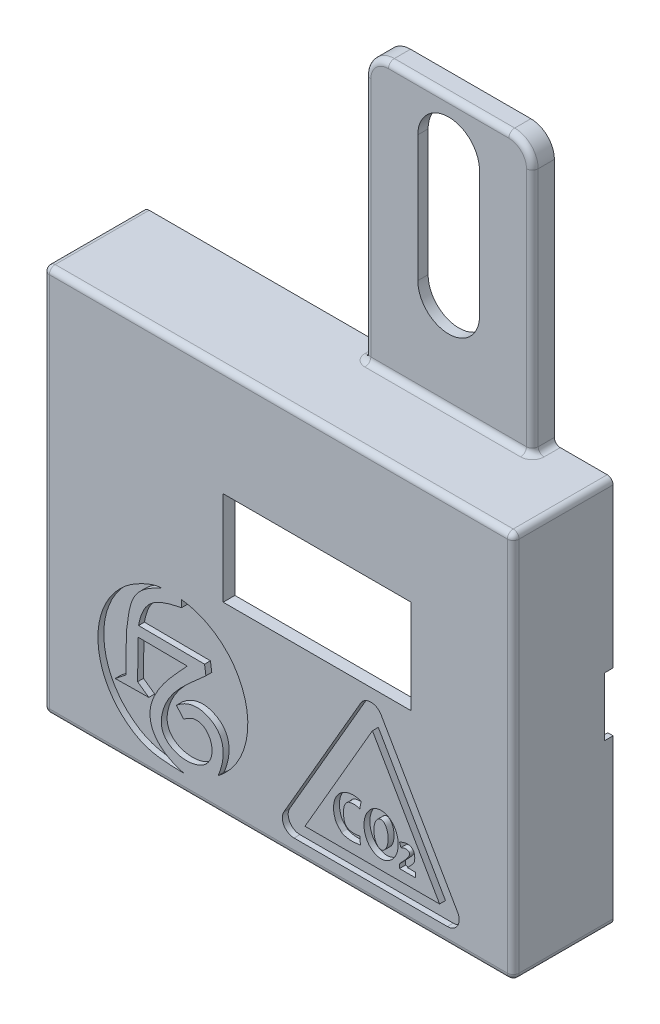
SolidWorks part; units mm, degrees
ref_plane "Front Plane" through (0, 0, 0) normal (0, 0, 1) x (1, 0, 0)
ref_plane "Top Plane" through (0, 0, 0) normal (0, 1, 0) x (1, 0, 0)
ref_plane "Right Plane" through (0, 0, 0) normal (1, 0, 0) x (0, 0, -1)
sketch "Croquis1" plane through (0, 0, 0) normal (0, 0, 1) x (1, 0, 0)
  line L3 (-40, -30.5) -> (40, -30.5)
  line L10 (-40, 35.5) -> (40, 35.5)
  line L12 (-40, 35.5) -> (-40, -30.5)
  line L14 (40, -30.5) -> (40, 35.5)
  point P1 (0, 0)
  dimension "D2" = 40
  dimension "D3" = 66
  dimension "D1" = 80
  dimension "D4" = 35.5
extrude "Saliente-Extruir2" add sketch "Croquis1" along normal blind 17
shell "Vaciado7" thickness 2
sketch "Croquis12" plane through (0, 0, 17) normal (0, 0, 1) x (1, 0, 0)
  line L1 (-9.4, 17) -> (22.6, 17)
  line L2 (-9.4, 17) -> (-9.4, 1)
  line L3 (-9.4, 1) -> (22.6, 1)
  line L4 (22.6, 17) -> (22.6, 1)
  line L5 (-9.4, 17) -> (22.6, 1) construction
  line L6 (-9.4, 1) -> (22.6, 17) construction
  line L9 (40, 35.5) -> (-40, 35.5) construction
  line L11 (40, -30.5) -> (40, 35.5) construction
  point P0 (6.6, 9)
  dimension "D1" = 17.4
  dimension "D2" = 32
  dimension "D3" = 16
  dimension "D4" = 18.5
extrude "Cortar-Extruir9" cut sketch "Croquis12" against normal up to next
sketch "Croquis29" plane through (0, 0, 0) normal (0, 0, -1) x (-1, 0, 0)
  line L9 (-1.5, 77.5) -> (-1.5, 35.5)
  line L10 (-5.5, 81.5) -> (-26, 81.5)
  line L14 (-15.75, 73.25) -> (-15.75, 51.75) construction
  line L15 (-10.5, 73.25) -> (-10.5, 51.75)
  line L16 (-21, 73.25) -> (-21, 51.75)
  line L17 (-30, 35.5) -> (-30, 77.5)
  line L19 (-1.5, 35.5) -> (-30, 35.5)
  line L20 (-40, 35.5) -> (40, 35.5) construction
  line L21 (-40, -30.5) -> (-40, 35.5) construction
  arc A8 (-10.5, 73.25) -> (-21, 73.25) centre (-15.75, 73.25) ccw
  arc A9 (-21, 51.75) -> (-10.5, 51.75) centre (-15.75, 51.75) ccw
  arc A10 (-30, 77.5) -> (-26, 81.5) centre (-26, 77.5) cw
  arc A11 (-1.5, 77.5) -> (-5.5, 81.5) centre (-5.5, 77.5) ccw
  point P2 (-15.75, 62.5)
  dimension "D3" = 10
  dimension "D4" = 4
  dimension "D7" = 5.25
  dimension "D2" = 4
  dimension "D1" = 28.5
  dimension "D5" = 46
  dimension "D6" = 21.5
  dimension "D8" = 14.25
  dimension "D9" = 8.25
extrude "Saliente-Extruir3" add sketch "Croquis29" against normal blind 3.75
sketch "Croquis14" plane through (0, 0, 0) normal (0, 0, -1) x (-1, 0, 0)
  line L8 (39.1, 34.6) -> (-2.4, 34.6)
  line L10 (-29.1, 34.6) -> (-39.1, 34.6)
  line L14 (39.1, 34.6) -> (-2.4, 34.6)
  line L16 (-29.1, 34.6) -> (-39.1, 34.6)
  line L17 (-39.1, -29.6) -> (39.1, -29.6)
  line L21 (-39.1, 34.6) -> (-39.1, -29.6)
  line L22 (-39.1, 34.6) -> (-39.1, -29.6)
  line L23 (39.1, -29.6) -> (39.1, 34.6)
  line L25 (-39.1, -29.6) -> (39.1, -29.6)
  line L28 (39.1, -29.6) -> (39.1, 34.6)
  line L33 (-2.4, 34.6) -> (-2.4, 77.5)
  line L34 (-2.4, 34.6) -> (-2.4, 77.5)
  line L35 (-5.5, 80.6) -> (-26, 80.6)
  line L36 (-5.5, 80.6) -> (-26, 80.6)
  line L37 (-29.1, 77.5) -> (-29.1, 34.6)
  line L38 (-29.1, 77.5) -> (-29.1, 34.6)
  arc A2 (-2.4, 77.5) -> (-5.5, 80.6) centre (-5.5, 77.5) ccw
  arc A9 (-2.4, 77.5) -> (-5.5, 80.6) centre (-5.5, 77.5) ccw
  arc A11 (-26, 80.6) -> (-29.1, 77.5) centre (-26, 77.5) ccw
  arc A12 (-26, 80.6) -> (-29.1, 77.5) centre (-26, 77.5) ccw
  dimension "D1" = 0.9
extrude "Cortar-Extruir11" cut sketch "Croquis14" against normal blind 2
sketch "Croquis16" plane through (-40, 0, 0) normal (-1, 0, 0) x (0, 0, 1)
  line L1 (2, -6.75) -> (12, -6.75)
  line L2 (2, -6.75) -> (2, -18.75)
  line L3 (2, -18.75) -> (12, -18.75)
  line L4 (12, -6.75) -> (12, -18.75)
  line L5 (2, -6.75) -> (12, -18.75) construction
  line L6 (2, -18.75) -> (12, -6.75) construction
  line L9 (17, 35.5) -> (17, -30.5) construction
  line L10 (17, -30.5) -> (0, -30.5) construction
  point P0 (7, -12.75)
  dimension "D1" = 5
  dimension "D2" = 11.75
  dimension "D3" = 12
  dimension "D4" = 10
extrude "Cortar-Extruir26" cut sketch "Croquis16" against normal up to next
sketch "Croquis19" plane through (0, 0, 17) normal (0, 0, 1) x (1, 0, 0)
  line L0 (105.4121, 47.0931) -> (337.4121, 47.0931) construction
  line L1 (-25.8792, -11.5578) -> (-25.9589, -18.0125)
  line L2 (-25.9589, -18.0125) -> (-27.7917, -19.4468)
  line L3 (-27.7917, -19.4468) -> (-22.0542, -19.3672)
  line L4 (-22.0542, -19.3672) -> (-23.9667, -18.0125)
  line L5 (-23.9667, -18.0125) -> (-23.887, -11.3984)
  line L6 (-23.887, -11.3984) -> (-15.5198, -11.4781)
  line L9 (-12.3323, -11.3187) -> (-12.5714, -9.725)
  line L10 (-12.5714, -9.725) -> (-23.8073, -9.6453)
  line L11 (-16.4761, -3.35) -> (-16.4761, -2.1547)
  line L12 (-17.3526, -18.1718) -> (-16.1573, -19.6062)
  arc A0 (-16.4761, -2.1547) -> (-10.2604, -25.025) centre (-17.9717, -14.8409) cw
  spline S0 degree 3 poles (-16.0776, -27.575) (-20.4729, -27.492) (-23.2734, -27.3961) (-26.6761, -24.2281) (-28.09, -22.9117) (-29.2916, -21.1122) (-29.9433, -19.2875) (-31.8667, -13.902) (-30.1633, -8.11) (-25.6401, -4.625) (-24.3726, -3.6484) (-21.5246, -2.1547) (-19.9026, -2.1547) knots 0 0 0 0 1 1 1 2 2 2 3 3 3 4 4 4 4
  spline S1 degree 3 poles (-19.9026, -2.1547) (-24.8924, -4.4832) (-25.2643, -6.27) (-25.8792, -11.5578) knots 0 0 0 0 1 1 1 1
  spline S2 degree 3 poles (-15.5198, -11.4781) (-17.5458, -13.7292) (-19.7899, -15.9184) (-21.0979, -18.65) (-23.283, -23.213) (-20.5069, -26.4677) (-16.0776, -27.575) knots 0 0 0 0 1 1 1 2 2 2 2
  spline S3 degree 3 poles (-10.2604, -25.025) (-9.0652, -22.1997) (-8.6121, -18.4678) (-12.2526, -17.0562) (-14.1508, -16.3202) (-15.9323, -16.9701) (-17.3526, -18.1718) knots 0 0 0 0 1 1 1 2 2 2 2
  spline S4 degree 3 poles (-16.1573, -19.6062) (-15.5995, -19.314) (-15.0975, -18.8713) (-14.4839, -18.7297) (-11.483, -18.0371) (-9.9609, -22.854) (-12.8104, -24.7062) (-15.4582, -26.4273) (-20.4502, -25.2692) (-19.9026, -21.2797) (-19.2896, -16.813) (-15.3841, -14.1357) (-12.3323, -11.3187) knots 0 0 0 0 1 1 1 2 2 2 3 3 3 4 4 4 4
  spline S5 degree 3 poles (-23.8073, -9.6453) (-22.9979, -5.2747) (-20.9378, -4.2423) (-16.4761, -3.35) knots 0 0 0 0 1 1 1 1
extrude "Cortar-Extruir18" cut sketch "Croquis19" against normal blind 1
sketch "Croquis20" plane through (0, 0, 17) normal (0, 0, 1) x (1, 0, 0)
  line L0 (-454.7792, 225.5349) -> (-56.1125, 225.5349) construction
  line L1 (14.0959, -16.6185) -> (13.8627, -17.8433)
  line L2 (13.8627, -21.8676) -> (13.9793, -23.1507)
  line L3 (21.9695, -22.4508) -> (23.3705, -22.4508)
  line L4 (23.3705, -22.4508) -> (23.3705, -23.2695)
  line L5 (23.3705, -23.2695) -> (20.6281, -23.2673)
  line L6 (20.8614, -20.0596) -> (20.6281, -19.3597)
  line L7 (16.0206, -5.2456) -> (27.4555, -25.0753)
  line L8 (27.4555, -25.0753) -> (4.531, -25.0753)
  line L9 (4.531, -25.0753) -> (16.0206, -5.2456)
  line L13 (17.4925, -2.1582) -> (30.5158, -24.7424)
  line L14 (28.7832, -27.7415) -> (2.6744, -27.7415)
  line L15 (0.9439, -24.7389) -> (14.0294, -2.1547)
  arc A0 (2.6744, -27.7415) -> (0.9439, -24.7389) centre (2.6744, -25.7415) cw
  arc A1 (30.5158, -24.7424) -> (28.7832, -27.7415) centre (28.7832, -25.7415) cw
  arc A2 (17.4925, -2.1582) -> (14.0294, -2.1547) centre (15.7599, -3.1573) ccw
  ellipse E0 centre (17.4962, -19.8248) end of major axis (17.4563, -23.3931) minor radius 2.9144
  ellipse E1 centre (17.4814, -19.8225) end of major axis (17.5087, -22.0549) minor radius 1.2154
  spline S0 degree 3 poles (13.9793, -23.1507) (12.8026, -23.2978) (11.8949, -23.4089) (10.8299, -22.9174) (10.78, -22.8943) (10.7521, -22.8396) (10.7132, -22.8007) (10.3295, -22.417) (9.997, -22.1807) (9.7801, -21.6926) (8.9336, -19.7881) (9.4906, -17.4289) (11.4714, -16.6185) (12.3307, -16.267) (13.2427, -16.2773) (14.0959, -16.6185) knots 0 0 0 0 1 1 1 2 2 2 3 3 3 4 4 4 5 5 5 5
  spline S1 degree 3 poles (13.8627, -17.8433) (13.6099, -17.785) (13.3631, -17.6875) (13.1045, -17.6684) (12.8323, -17.6482) (12.5584, -17.6906) (12.2879, -17.7267) (10.871, -17.9156) (10.9607, -20.2139) (11.2965, -21.1094) (11.6855, -22.1468) (13.0408, -22.0046) (13.8627, -21.8676) knots 0 0 0 0 1 1 1 2 2 2 3 3 3 4 4 4 4
  spline S2 degree 3 poles (20.6281, -19.3597) (22.2168, -18.5654) (23.4507, -18.9531) (23.1943, -20.8761) (23.1277, -21.3757) (22.2517, -22.1429) (21.9695, -22.4508) knots 0 0 0 0 1 1 1 2 2 2 2
  spline S3 degree 3 poles (20.6281, -23.2673) (20.6475, -23.0146) (20.5866, -22.7421) (20.6864, -22.5091) (20.8, -22.244) (23.6377, -19.8263) (21.6196, -19.8263) (21.2133, -19.8263) (21.1983, -19.9753) (20.8614, -20.0596) knots 0 0 0 0 1 1 1 2 2 2 3 3 3 3
  dimension "D1" = 2
extrude "Cortar-Extruir24" cut sketch "Croquis20" against normal blind 1 contours L13 A2 L15 A0 L14 A1 L8 L9 L7 | S1 L1 S0 L2 | E0 E1 | S3 L5 L4 L3 S2 L6
sketch "Croquis27" plane through (40, 0, 0) normal (1, 0, 0) x (0, 0, -1)
  line L0 (-17, -30.5) -> (0, -30.5) construction
  line L1 (-1.5, 7.5) -> (0, 7.5)
  line L2 (-1.5, 7.5) -> (-1.5, -2.5)
  line L3 (-1.5, -2.5) -> (0, -2.5)
  line L4 (0, 7.5) -> (0, -2.5)
  line L7 (-17, -30.5) -> (-17, 35.5) construction
  dimension "D1" = 1.5
  dimension "D2" = 10
  dimension "D3" = 28
  dimension "D4" = 15.5
extrude "Cortar-Extruir25" cut sketch "Croquis27" against normal up to next
fillet "Redondeo3" radius 1 16 edges at (15.75, 35.5, 3.75) (1.5, 56.5, 3.75) (2.6716, 80.3284, 3.75) (30, 56.5, 3.75) (28.8284, 80.3284, 3.75) (15.75, 81.5, 3.75) (40, 2.5, 17) (0, -30.5, 17) (-40, 2.5, 17) (0, 35.5, 17) (40, -30.5, 8.5) (-40, -30.5, 8.5) (-40, 35.5, 8.5) (1.5, 35.5, 1.875) (30, 35.5, 1.875) (40, 35.5, 8.5)
